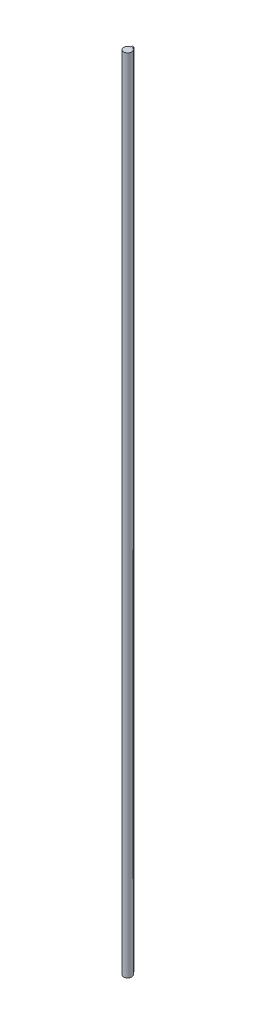
SolidWorks part; units mm, degrees
ref_plane "前视基准面" through (0, 0, 0) normal (0, 0, 1) x (1, 0, 0)
ref_plane "上视基准面" through (0, 0, 0) normal (0, 1, 0) x (1, 0, 0)
ref_plane "右视基准面" through (0, 0, 0) normal (1, 0, 0) x (0, 0, -1)
sketch "草图1" plane through (0, 0, 0) normal (0, 1, 0) x (1, 0, 0)
  line L1 (0, -6.6512) -> (0, 18.474) construction
  line L2 (-2, 9.798) -> (-2, 13.798)
  line L3 (-2, 13.798) -> (2, 13.798)
  line L4 (2, 9.798) -> (2, 13.798)
  arc A0 (-2, 9.798) -> (2, 9.798) centre (0, 0) ccw
  point P10 (0, 13.798)
  dimension "D1" = 4
  dimension "D3" = 10
  dimension "D2" = 4
extrude "凸台-拉伸1" add sketch "草图1" along normal blind 2000
